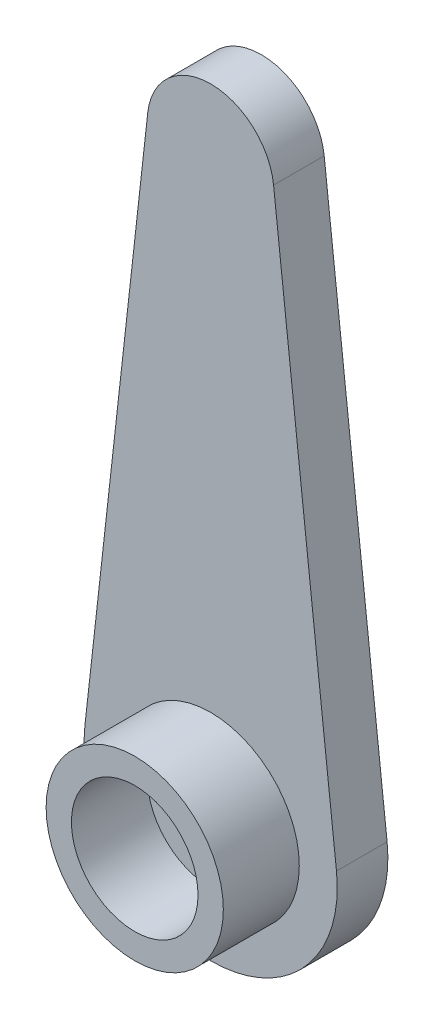
SolidWorks part; units mm, degrees
ref_plane "前视基准面" through (0, 0, 0) normal (0, 0, 1) x (1, 0, 0)
ref_plane "上视基准面" through (0, 0, 0) normal (0, 1, 0) x (1, 0, 0)
ref_plane "右视基准面" through (0, 0, 0) normal (1, 0, 0) x (0, 0, -1)
sketch "草图1" plane through (0, 0, 0) normal (0, 0, 1) x (1, 0, 0)
  line L0 (-4.969, 0.5556) -> (-2.4845, 22.7778)
  line L1 (0, 20) -> (0, 0) construction
  line L2 (4.969, 0.5556) -> (2.4845, 22.7778)
  arc A0 (-4.969, 0.5556) -> (4.969, 0.5556) centre (0, 0) ccw
  arc A1 (2.4845, 22.7778) -> (-2.4845, 22.7778) centre (0, 22.5) ccw
  dimension "D1" = 10
  dimension "D2" = 5
  dimension "D3" = 22.5
extrude "凸台-拉伸1" add sketch "草图1" along normal blind 2
sketch "草图2" plane through (0, 0, 2) normal (0, 0, 1) x (1, 0, 0)
  circle A0 centre (0, 0) radius 3.5
  circle A1 centre (0, 0) radius 2.5
  dimension "D1" = 5
  dimension "D2" = 7
extrude "凸台-拉伸2" add sketch "草图2" along normal blind 3
